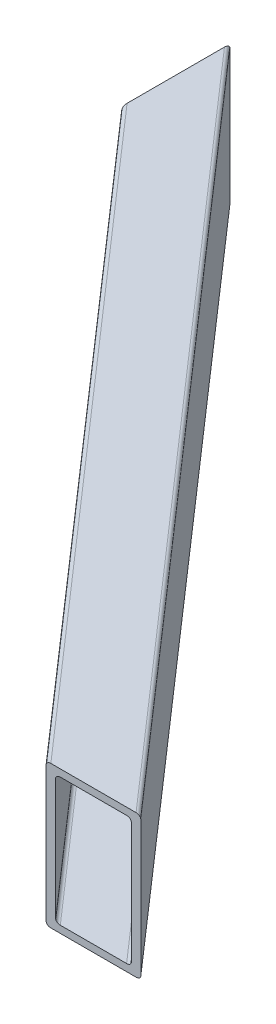
SolidWorks part; units mm, degrees
ref_plane "Plan de face" through (0, 0, 0) normal (0, 0, 1) x (1, 0, 0)
ref_plane "Plan de dessus" through (0, 0, 0) normal (0, 1, 0) x (1, 0, 0)
ref_plane "Plan de droite" through (0, 0, 0) normal (1, 0, 0) x (0, 0, -1)
sketch "Esquisse1" plane through (0, 0, 0) normal (0, 1, 0) x (1, 0, 0)
  line L0 (0, 0) -> (0, 339.2563) construction
  line L1 (0, 339.2563) -> (296.8493, 0)
  line L2 (296.8493, 0) -> (0, 0) construction
  line L3 (296.8493, 0) -> (350, 0)
  line L4 (350, 0) -> (0, 400)
  line L5 (0, 339.2563) -> (0, 400)
  dimension "D1" = 40
  dimension "D2" = 350
  dimension "D3" = 400
extrude "Boss.-Extru.1" add sketch "Esquisse1" along normal blind 80
shell "Coque1" thickness 4
ref_plane "Plan1" through (128.7223, 0, 147.1111) normal (-0.6585, 0, -0.7526) x (0, -1, 0)
sketch "Esquisse2" plane through (128.7223, 0, 147.1111) normal (-0.6585, 0, -0.7526) x (0, -1, 0)
  line L0 (-80, -263.4018) -> (-80, -223.4018) construction
  line L1 (-76, -227.4018) -> (-4, -227.4018)
  line L2 (-76, -227.4018) -> (-76, -259.4018)
  line L3 (-76, -259.4018) -> (-4, -259.4018)
  line L4 (-4, -227.4018) -> (-4, -259.4018)
  line L5 (-80, -223.4018) -> (0, -223.4018) construction
  line L6 (-80, -263.4018) -> (0, -263.4018) construction
  line L7 (0, -263.4018) -> (0, -223.4018) construction
  dimension "D1" = 4
  dimension "D2" = 4
  dimension "D3" = 4
  dimension "D4" = 4
extrude "Enlèv. mat.-Extru.1" cut sketch "Esquisse2" against normal through all both and the other way through all
fillet "Congé1" radius 2 8 edges at (148.4246, 80, -169.6282) (172.3425, 76, -196.9628) (151.0822, 76, -172.6653) (151.0822, 4, -172.6653) (172.3425, 4, -196.9628) (175, 80, -200) (148.4246, 0, -169.6282) (175, 0, -200)
